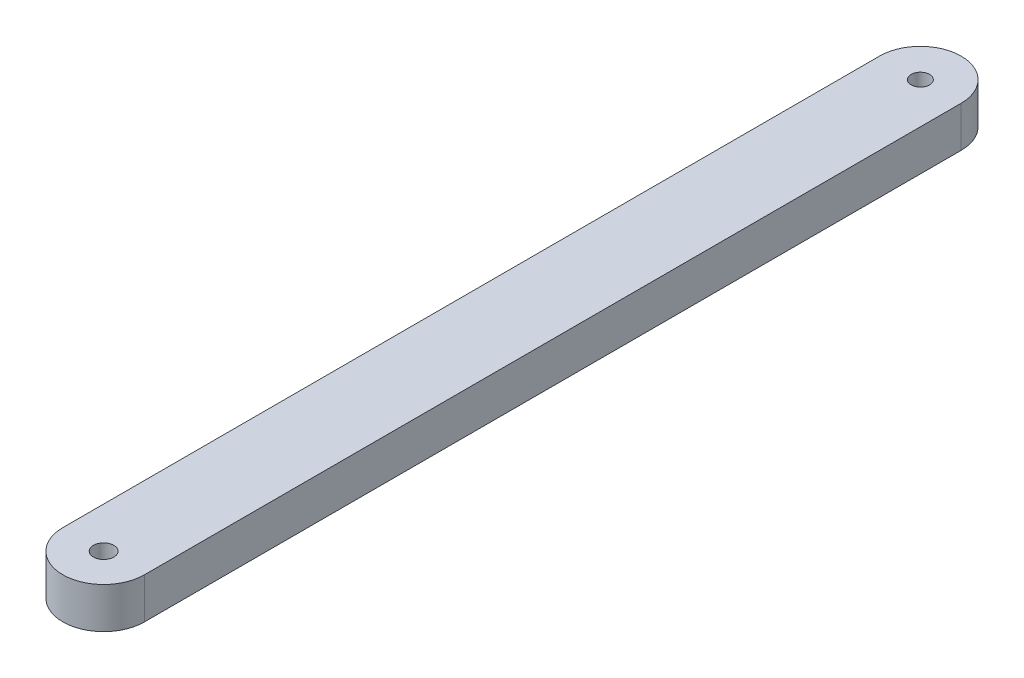
SolidWorks part; units mm, degrees
ref_plane "Front Plane" through (0, 0, 0) normal (0, 0, 1) x (1, 0, 0)
ref_plane "Top Plane" through (0, 0, 0) normal (0, 1, 0) x (1, 0, 0)
ref_plane "Right Plane" through (0, 0, 0) normal (1, 0, 0) x (0, 0, -1)
sketch "Sketch1" plane through (0, 0, 0) normal (0, 1, 0) x (1, 0, 0)
  line L0 (-10, 100) -> (10, 100) construction
  line L2 (10, -100) -> (10, 100)
  line L4 (-10, -100) -> (-10, 100)
  line L5 (10, -100) -> (-10, 100) construction
  line L6 (10, 100) -> (-10, -100) construction
  line L8 (-1.5875, 98.4125) -> (1.5875, 98.4125)
  line L9 (-1.5875, 98.4125) -> (-1.5875, 101.5875)
  line L10 (-1.5875, 101.5875) -> (1.5875, 101.5875)
  line L11 (1.5875, 98.4125) -> (1.5875, 101.5875)
  line L12 (-1.5875, 98.4125) -> (1.5875, 101.5875) construction
  line L13 (-1.5875, 101.5875) -> (1.5875, 98.4125) construction
  arc A0 (-10, 100) -> (10, 100) centre (0, 100) cw
  arc A1 (10, -100) -> (-10, -100) centre (0, -100) cw
  circle A2 centre (0, -100) radius 2.5
  circle A3 centre (0, 100) radius 2.2451
  point P0 (0, 0)
  dimension "D3" = 5
  dimension "D1" = 200
  dimension "D2" = 20
  dimension "D4" = 3.175
extrude "Boss-Extrude1" add sketch "Sketch1" along normal blind 10 contours A1 L2 A0 L4 A3 A2
